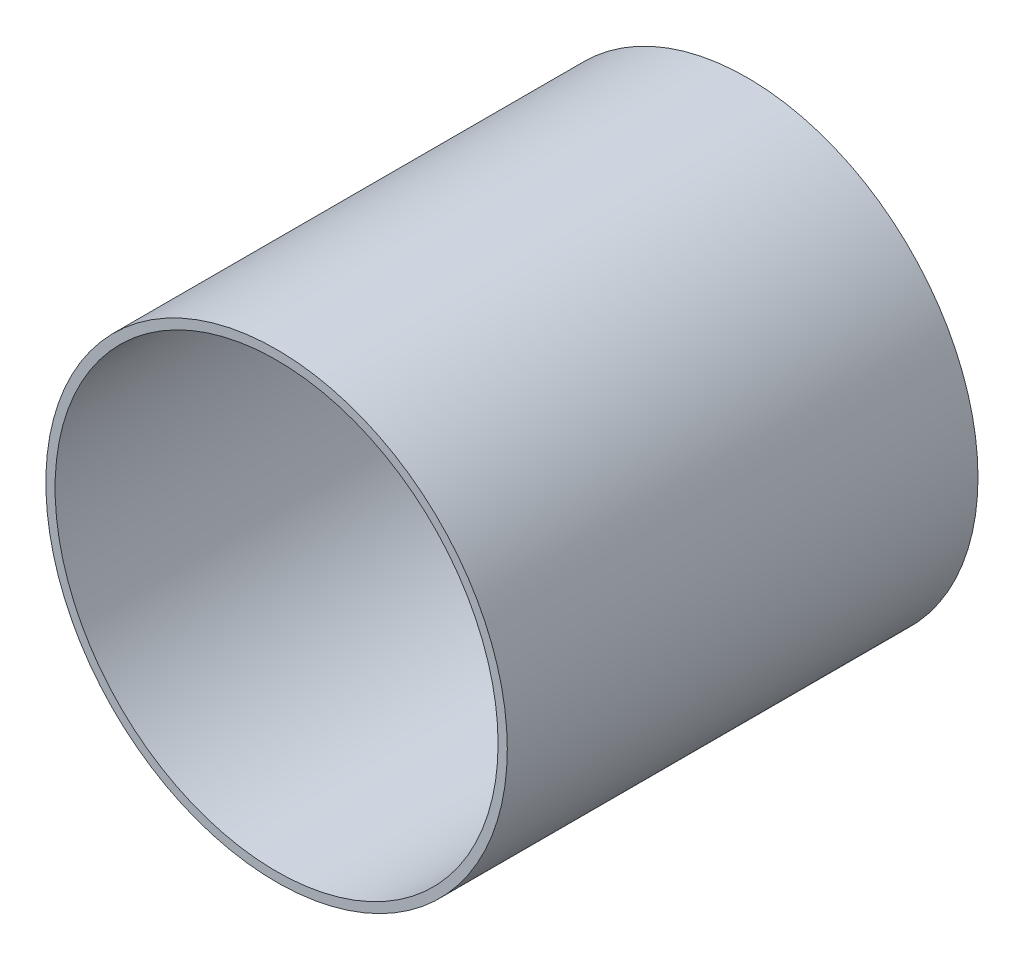
SolidWorks part; units mm, degrees
ref_plane "Front Plane" through (0, 0, 0) normal (0, 0, 1) x (1, 0, 0)
ref_plane "Top Plane" through (0, 0, 0) normal (0, 1, 0) x (1, 0, 0)
ref_plane "Right Plane" through (0, 0, 0) normal (1, 0, 0) x (0, 0, -1)
sketch "Sketch1" plane through (0, 0, 0) normal (0, 0, 1) x (1, 0, 0)
  circle A0 centre (0, 0) radius 75
  dimension "D1" = 150
extrude "Boss-Extrude1" add sketch "Sketch1" along normal blind 3
sketch "Sketch2" plane through (0, 0, 3) normal (0, 0, 1) x (1, 0, 0)
  circle A0 centre (0, 0) radius 75
  circle A1 centre (0, 0) radius 72
  dimension "D1" = 144
  dimension "D2" = 150
extrude "Boss-Extrude2" add sketch "Sketch2" along normal blind 150
sketch "Sketch3" plane through (0, 0, 3) normal (0, 0, 1) x (1, 0, 0)
  circle A0 centre (30, 0) radius 5
  circle A1 centre (-30, 0) radius 5
  dimension "D3" = 10
  dimension "D4" = 10
  dimension "D1" = 30
  dimension "D2" = 30
extrude "Cut-Extrude1" cut sketch "Sketch3" against normal blind 150
